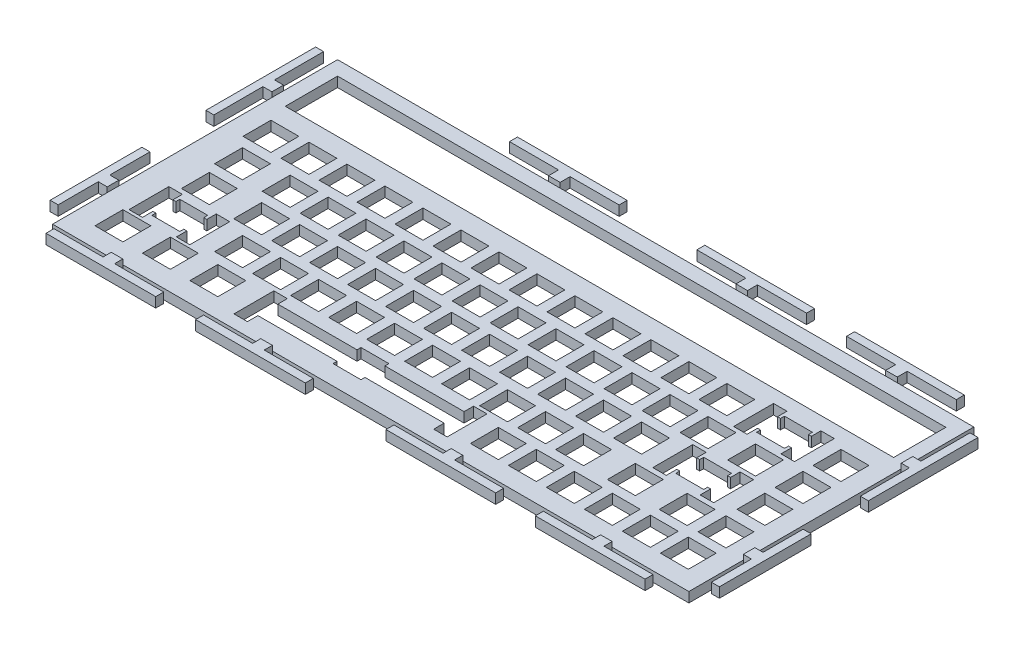
SolidWorks part; units mm, degrees
ref_plane "Front Plane" through (0, 0, 0) normal (0, 0, 1) x (1, 0, 0)
ref_plane "Top Plane" through (0, 0, 0) normal (0, 1, 0) x (1, 0, 0)
ref_plane "Right Plane" through (0, 0, 0) normal (1, 0, 0) x (0, 0, -1)
sketch "Sketch1" plane through (0, 0, 0) normal (0, 1, 0) x (1, 0, 0)
  line L2 (-75.7545, 37.9956) -> (-61.7545, 37.9956)
  line L3 (-94.8265, 37.9956) -> (-80.8265, 37.9956)
  line L4 (-94.8265, 37.9956) -> (-94.8265, 51.9956)
  line L5 (-94.8265, 51.9956) -> (-80.8265, 51.9956)
  line L6 (-80.8265, 37.9956) -> (-80.8265, 51.9956)
  line L7 (-75.7545, 37.9956) -> (-75.7545, 51.9956)
  line L8 (-75.7545, 51.9956) -> (-61.7545, 51.9956)
  line L9 (-61.7545, 37.9956) -> (-61.7545, 51.9956)
  line L10 (133.7495, 37.9956) -> (147.7495, 37.9956)
  line L11 (-37.6545, 37.9956) -> (-23.6545, 37.9956)
  line L12 (-56.7045, 37.9956) -> (-42.7045, 37.9956)
  line L13 (-56.7045, 37.9956) -> (-56.7045, 51.9956)
  line L14 (-56.7045, 51.9956) -> (-42.7045, 51.9956)
  line L15 (-42.7045, 37.9956) -> (-42.7045, 51.9956)
  line L16 (-37.6545, 37.9956) -> (-37.6545, 51.9956)
  line L17 (-37.6545, 51.9956) -> (-23.6545, 51.9956)
  line L18 (-23.6545, 37.9956) -> (-23.6545, 51.9956)
  line L19 (133.7495, 37.9956) -> (133.7495, 51.9956)
  line L20 (133.7495, 51.9956) -> (147.7495, 51.9956)
  line L21 (0.4455, 37.9956) -> (14.4455, 37.9956)
  line L22 (-18.6045, 37.9956) -> (-4.6045, 37.9956)
  line L23 (-18.6045, 37.9956) -> (-18.6045, 51.9956)
  line L24 (-18.6045, 51.9956) -> (-4.6045, 51.9956)
  line L25 (-4.6045, 37.9956) -> (-4.6045, 51.9956)
  line L26 (0.4455, 37.9956) -> (0.4455, 51.9956)
  line L27 (0.4455, 51.9956) -> (14.4455, 51.9956)
  line L28 (14.4455, 37.9956) -> (14.4455, 51.9956)
  line L29 (147.7495, 37.9956) -> (147.7495, 51.9956)
  line L30 (38.5455, 37.9956) -> (52.5455, 37.9956)
  line L31 (19.4955, 37.9956) -> (33.4955, 37.9956)
  line L32 (19.4955, 37.9956) -> (19.4955, 51.9956)
  line L33 (19.4955, 51.9956) -> (33.4955, 51.9956)
  line L34 (33.4955, 37.9956) -> (33.4955, 51.9956)
  line L35 (38.5455, 37.9956) -> (38.5455, 51.9956)
  line L36 (38.5455, 51.9956) -> (52.5455, 51.9956)
  line L37 (52.5455, 37.9956) -> (52.5455, 51.9956)
  line L38 (147.7495, 44.9956) -> (154.1495, 44.9956) construction
  line L39 (167.1835, 18.9456) -> (181.1835, 18.9456)
  line L40 (167.1835, 18.9456) -> (167.1835, 32.9456)
  line L41 (76.6455, 37.9956) -> (90.6455, 37.9956)
  line L42 (57.5955, 37.9956) -> (71.5955, 37.9956)
  line L43 (57.5955, 37.9956) -> (57.5955, 51.9956)
  line L44 (57.5955, 51.9956) -> (71.5955, 51.9956)
  line L45 (71.5955, 37.9956) -> (71.5955, 51.9956)
  line L46 (76.6455, 37.9956) -> (76.6455, 51.9956)
  line L47 (76.6455, 51.9956) -> (90.6455, 51.9956)
  line L48 (90.6455, 37.9956) -> (90.6455, 51.9956)
  line L49 (167.1835, 32.9456) -> (181.1835, 32.9456)
  line L50 (114.7225, 37.9956) -> (128.7225, 37.9956)
  line L51 (95.6955, 37.9956) -> (109.6955, 37.9956)
  line L52 (95.6955, 37.9956) -> (95.6955, 51.9956)
  line L53 (95.6955, 51.9956) -> (109.6955, 51.9956)
  line L54 (109.6955, 37.9956) -> (109.6955, 51.9956)
  line L55 (114.7225, 37.9956) -> (114.7225, 51.9956)
  line L56 (114.7225, 51.9956) -> (128.7225, 51.9956)
  line L57 (128.7225, 37.9956) -> (128.7225, 51.9956)
  line L58 (181.1835, 18.9456) -> (181.1835, 32.9456)
  line L59 (157.3735, 25.9456) -> (167.1835, 25.9456) construction
  line L73 (162.3995, 52.2456) -> (176.3995, 52.2456)
  line L75 (176.3995, 38.2456) -> (162.3995, 38.2456)
  line L77 (176.3995, 52.2456) -> (176.3995, 50.2456)
  line L78 (176.3995, 50.2456) -> (177.8995, 50.2456)
  line L79 (177.8995, 50.2456) -> (177.8995, 54.9956)
  line L80 (177.8995, 54.9956) -> (184.6495, 54.9956)
  line L81 (184.6495, 54.9956) -> (184.6495, 34.9956)
  line L82 (184.6495, 34.9956) -> (177.8995, 34.9956)
  line L83 (177.8995, 34.9956) -> (177.8995, 40.2456)
  line L84 (177.8995, 40.2456) -> (176.3995, 40.2456)
  line L85 (176.3995, 40.2456) -> (176.3995, 38.2456)
  line L86 (162.3995, 52.2456) -> (162.3995, 50.2456)
  line L87 (160.8995, 54.9956) -> (160.8995, 50.2456)
  line L88 (160.8995, 50.2456) -> (162.3995, 50.2456)
  line L89 (160.8995, 54.9956) -> (154.1495, 54.9956)
  line L90 (154.1495, 54.9956) -> (154.1495, 34.9956)
  line L91 (154.1495, 34.9956) -> (160.8995, 34.9956)
  line L92 (160.8995, 34.9956) -> (160.8995, 40.2456)
  line L93 (160.8995, 40.2456) -> (162.3995, 40.2456)
  line L94 (162.3995, 40.2456) -> (162.3995, 38.2456)
  line L116 (-47.1265, 18.9456) -> (-33.1265, 18.9456)
  line L117 (-66.1765, 18.9456) -> (-52.1765, 18.9456)
  line L118 (-66.1765, 18.9456) -> (-66.1765, 32.9456)
  line L119 (-66.1765, 32.9456) -> (-52.1765, 32.9456)
  line L120 (-52.1765, 18.9456) -> (-52.1765, 32.9456)
  line L121 (-47.1265, 18.9456) -> (-47.1265, 32.9456)
  line L122 (-47.1265, 32.9456) -> (-33.1265, 32.9456)
  line L123 (-33.1265, 18.9456) -> (-33.1265, 32.9456)
  line L125 (-9.0515, 18.9456) -> (4.9485, 18.9456)
  line L126 (-28.0765, 18.9456) -> (-14.0765, 18.9456)
  line L127 (-28.0765, 18.9456) -> (-28.0765, 32.9456)
  line L128 (-28.0765, 32.9456) -> (-14.0765, 32.9456)
  line L129 (-14.0765, 18.9456) -> (-14.0765, 32.9456)
  line L130 (-9.0515, 18.9456) -> (-9.0515, 32.9456)
  line L131 (-9.0515, 32.9456) -> (4.9485, 32.9456)
  line L132 (4.9485, 18.9456) -> (4.9485, 32.9456)
  line L135 (29.0735, 18.9456) -> (43.0735, 18.9456)
  line L136 (9.9485, 18.9456) -> (23.9485, 18.9456)
  line L137 (9.9485, 18.9456) -> (9.9485, 32.9456)
  line L138 (9.9485, 32.9456) -> (23.9485, 32.9456)
  line L139 (23.9485, 18.9456) -> (23.9485, 32.9456)
  line L140 (29.0735, 18.9456) -> (29.0735, 32.9456)
  line L141 (29.0735, 32.9456) -> (43.0735, 32.9456)
  line L142 (43.0735, 18.9456) -> (43.0735, 32.9456)
  line L144 (67.1485, 18.9456) -> (81.1485, 18.9456)
  line L145 (48.1235, 18.9456) -> (62.1235, 18.9456)
  line L146 (48.1235, 18.9456) -> (48.1235, 32.9456)
  line L147 (48.1235, 32.9456) -> (62.1235, 32.9456)
  line L148 (62.1235, 18.9456) -> (62.1235, 32.9456)
  line L149 (67.1485, 18.9456) -> (67.1485, 32.9456)
  line L150 (67.1485, 32.9456) -> (81.1485, 32.9456)
  line L151 (81.1485, 18.9456) -> (81.1485, 32.9456)
  line L152 (159.9865, 14.1456) -> (173.9865, 14.1456)
  line L153 (-42.3635, -0.1044) -> (-28.3635, -0.1044)
  line L154 (-61.4135, -0.1044) -> (-47.4135, -0.1044)
  line L155 (105.2735, 18.9456) -> (119.2735, 18.9456)
  line L156 (86.2235, 18.9456) -> (100.2235, 18.9456)
  line L157 (86.2235, 18.9456) -> (86.2235, 32.9456)
  line L158 (86.2235, 32.9456) -> (100.2235, 32.9456)
  line L159 (100.2235, 18.9456) -> (100.2235, 32.9456)
  line L160 (105.2735, 18.9456) -> (105.2735, 32.9456)
  line L161 (105.2735, 32.9456) -> (119.2735, 32.9456)
  line L162 (119.2735, 18.9456) -> (119.2735, 32.9456)
  line L163 (-61.4135, -0.1044) -> (-61.4135, 13.8956)
  line L172 (-94.8265, 37.9956) -> (-94.8265, 32.9456) construction
  line L173 (-61.4135, 13.8956) -> (-47.4135, 13.8956)
  line L174 (-47.4135, -0.1044) -> (-47.4135, 13.8956)
  line L175 (-90.0635, 18.9456) -> (-76.0635, 18.9456)
  line L176 (-90.0635, 18.9456) -> (-90.0635, 32.9456)
  line L177 (-90.0635, 32.9456) -> (-76.0635, 32.9456)
  line L178 (-76.0635, 18.9456) -> (-76.0635, 32.9456)
  line L179 (-94.8265, 32.9456) -> (-90.0635, 32.9456) construction
  line L180 (124.3235, 18.9456) -> (138.3235, 18.9456)
  line L185 (124.3235, 18.9456) -> (124.3235, 32.9456)
  line L186 (124.3235, 32.9456) -> (138.3235, 32.9456)
  line L187 (138.3235, 18.9456) -> (138.3235, 32.9456)
  line L188 (-42.3635, -0.1044) -> (-42.3635, 13.8956)
  line L189 (143.3735, 18.9456) -> (157.3735, 18.9456)
  line L190 (143.3735, 18.9456) -> (143.3735, 32.9456)
  line L191 (143.3735, 32.9456) -> (157.3735, 32.9456)
  line L192 (157.3735, 18.9456) -> (157.3735, 32.9456)
  line L193 (-42.3635, 13.8956) -> (-28.3635, 13.8956)
  line L194 (-28.3635, -0.1044) -> (-28.3635, 13.8956)
  line L195 (-4.2635, -0.1044) -> (9.7365, -0.1044)
  line L196 (-23.3135, -0.1044) -> (-9.3135, -0.1044)
  line L197 (-23.3135, -0.1044) -> (-23.3135, 13.8956)
  line L198 (-23.3135, 13.8956) -> (-9.3135, 13.8956)
  line L199 (-9.3135, -0.1044) -> (-9.3135, 13.8956)
  line L200 (-4.2635, -0.1044) -> (-4.2635, 13.8956)
  line L201 (-4.2635, 13.8956) -> (9.7365, 13.8956)
  line L202 (9.7365, -0.1044) -> (9.7365, 13.8956)
  line L203 (33.8365, -0.1044) -> (47.8365, -0.1044)
  line L204 (14.7865, -0.1044) -> (28.7865, -0.1044)
  line L205 (14.7865, -0.1044) -> (14.7865, 13.8956)
  line L206 (14.7865, 13.8956) -> (28.7865, 13.8956)
  line L207 (28.7865, -0.1044) -> (28.7865, 13.8956)
  line L208 (33.8365, -0.1044) -> (33.8365, 13.8956)
  line L209 (33.8365, 13.8956) -> (47.8365, 13.8956)
  line L210 (47.8365, -0.1044) -> (47.8365, 13.8956)
  line L211 (71.9365, -0.1044) -> (85.9365, -0.1044)
  line L212 (52.8865, -0.1044) -> (66.8865, -0.1044)
  line L213 (52.8865, -0.1044) -> (52.8865, 13.8956)
  line L214 (52.8865, 13.8956) -> (66.8865, 13.8956)
  line L215 (66.8865, -0.1044) -> (66.8865, 13.8956)
  line L216 (71.9365, -0.1044) -> (71.9365, 13.8956)
  line L217 (71.9365, 13.8956) -> (85.9365, 13.8956)
  line L218 (85.9365, -0.1044) -> (85.9365, 13.8956)
  line L219 (110.0365, -0.1044) -> (124.0365, -0.1044)
  line L220 (90.9865, -0.1044) -> (104.9865, -0.1044)
  line L221 (90.9865, -0.1044) -> (90.9865, 13.8956)
  line L222 (90.9865, 13.8956) -> (104.9865, 13.8956)
  line L223 (104.9865, -0.1044) -> (104.9865, 13.8956)
  line L224 (110.0365, -0.1044) -> (110.0365, 13.8956)
  line L225 (110.0365, 13.8956) -> (124.0365, 13.8956)
  line L226 (124.0365, -0.1044) -> (124.0365, 13.8956)
  line L227 (-87.6075, -0.1044) -> (-73.6075, -0.1044)
  line L228 (-87.6075, -0.1044) -> (-87.6075, 13.8956)
  line L229 (-87.6075, 13.8956) -> (-73.6075, 13.8956)
  line L230 (-73.6075, -0.1044) -> (-73.6075, 13.8956)
  line L231 (-90.0635, 18.9456) -> (-90.0635, 13.8956) construction
  line L232 (129.0865, -0.1044) -> (143.0865, -0.1044)
  line L233 (129.0865, -0.1044) -> (129.0865, 13.8956)
  line L234 (129.0865, 13.8956) -> (143.0865, 13.8956)
  line L235 (143.0865, -0.1044) -> (143.0865, 13.8956)
  line L240 (-90.0635, 13.8956) -> (-87.6075, 13.8956) construction
  line L241 (173.9865, 0.1456) -> (159.9865, 0.1456)
  line L242 (173.9865, 14.1456) -> (173.9865, 12.1456)
  line L243 (173.9865, 12.1456) -> (175.4865, 12.1456)
  line L244 (175.4865, 12.1456) -> (175.4865, 16.8956)
  line L245 (175.4865, 16.8956) -> (182.2365, 16.8956)
  line L246 (182.2365, 16.8956) -> (182.2365, -3.1044)
  line L247 (182.2365, -3.1044) -> (175.4865, -3.1044)
  line L248 (175.4865, -3.1044) -> (175.4865, 2.1456)
  line L249 (175.4865, 2.1456) -> (173.9865, 2.1456)
  line L250 (173.9865, 2.1456) -> (173.9865, 0.1456)
  line L251 (159.9865, 14.1456) -> (159.9865, 12.1456)
  line L252 (158.4865, 16.8956) -> (158.4865, 12.1456)
  line L253 (158.4865, 12.1456) -> (159.9865, 12.1456)
  line L254 (158.4865, 16.8956) -> (151.7365, 16.8956)
  line L255 (151.7365, 16.8956) -> (151.7365, -3.1044)
  line L256 (151.7365, -3.1044) -> (158.4865, -3.1044)
  line L257 (158.4865, -3.1044) -> (158.4865, 2.1456)
  line L258 (158.4865, 2.1456) -> (159.9865, 2.1456)
  line L259 (159.9865, 2.1456) -> (159.9865, 0.1456)
  line L260 (143.0865, 12.1456) -> (151.7365, 12.1456) construction
  line L262 (-32.8385, -19.1544) -> (-18.8385, -19.1544)
  line L263 (-51.8885, -19.1544) -> (-37.8885, -19.1544)
  line L264 (-51.8885, -19.1544) -> (-51.8885, -5.1544)
  line L265 (-51.8885, -5.1544) -> (-37.8885, -5.1544)
  line L266 (-37.8885, -19.1544) -> (-37.8885, -5.1544)
  line L267 (-32.8385, -19.1544) -> (-32.8385, -5.1544)
  line L268 (-32.8385, -5.1544) -> (-18.8385, -5.1544)
  line L269 (-18.8385, -19.1544) -> (-18.8385, -5.1544)
  line L270 (5.2615, -19.1544) -> (19.2615, -19.1544)
  line L271 (-13.7885, -19.1544) -> (0.2115, -19.1544)
  line L272 (-13.7885, -19.1544) -> (-13.7885, -5.1544)
  line L273 (-13.7885, -5.1544) -> (0.2115, -5.1544)
  line L274 (0.2115, -19.1544) -> (0.2115, -5.1544)
  line L275 (5.2615, -19.1544) -> (5.2615, -5.1544)
  line L276 (5.2615, -5.1544) -> (19.2615, -5.1544)
  line L277 (19.2615, -19.1544) -> (19.2615, -5.1544)
  line L278 (43.3615, -19.1544) -> (57.3615, -19.1544)
  line L279 (24.3115, -19.1544) -> (38.3115, -19.1544)
  line L280 (24.3115, -19.1544) -> (24.3115, -5.1544)
  line L281 (24.3115, -5.1544) -> (38.3115, -5.1544)
  line L282 (38.3115, -19.1544) -> (38.3115, -5.1544)
  line L283 (43.3615, -19.1544) -> (43.3615, -5.1544)
  line L284 (43.3615, -5.1544) -> (57.3615, -5.1544)
  line L285 (57.3615, -19.1544) -> (57.3615, -5.1544)
  line L286 (81.4615, -19.6544) -> (95.4615, -19.6544)
  line L287 (62.4115, -19.6544) -> (76.4115, -19.6544)
  line L288 (62.4115, -19.6544) -> (62.4115, -5.6544)
  line L289 (62.4115, -5.6544) -> (76.4115, -5.6544)
  line L290 (76.4115, -19.6544) -> (76.4115, -5.6544)
  line L291 (81.4615, -19.6544) -> (81.4615, -5.6544)
  line L292 (81.4615, -5.6544) -> (95.4615, -5.6544)
  line L293 (95.4615, -19.6544) -> (95.4615, -5.6544)
  line L294 (119.5615, -19.6544) -> (133.5615, -19.6544)
  line L295 (100.5115, -19.6544) -> (114.5115, -19.6544)
  line L296 (100.5115, -19.6544) -> (100.5115, -5.6544)
  line L297 (100.5115, -5.6544) -> (114.5115, -5.6544)
  line L298 (114.5115, -19.6544) -> (114.5115, -5.6544)
  line L299 (119.5615, -19.6544) -> (119.5615, -5.6544)
  line L300 (119.5615, -5.6544) -> (133.5615, -5.6544)
  line L301 (133.5615, -19.6544) -> (133.5615, -5.6544)
  line L306 (-83.3445, -5.1544) -> (-69.3445, -5.1544)
  line L307 (145.5235, -19.6544) -> (159.5235, -19.6544)
  line L308 (145.5235, -19.6544) -> (145.5235, -5.6544)
  line L309 (145.5235, -5.6544) -> (159.5235, -5.6544)
  line L310 (159.5235, -19.6544) -> (159.5235, -5.6544)
  line L311 (-69.3445, -19.1544) -> (-83.3445, -19.1544)
  line L331 (171.4855, -19.6544) -> (185.4855, -19.6544)
  line L332 (171.4855, -19.6544) -> (171.4855, -5.6544)
  line L333 (171.4855, -5.6544) -> (185.4855, -5.6544)
  line L334 (185.4855, -19.6544) -> (185.4855, -5.6544)
  line L335 (159.5235, -12.6544) -> (171.4855, -12.6544) construction
  line L336 (-61.4135, -0.1044) -> (-61.4135, -5.1544) construction
  line L337 (-61.4135, -5.1544) -> (-51.8885, -5.1544) construction
  line L338 (-104.4215, 94.9896) -> (-117.5239, 94.9896) construction
  line L339 (-97.2765, 61.6456) -> (207.7235, 61.6456)
  line L340 (190.9955, 18.9456) -> (204.9955, 18.9456)
  line L341 (190.9955, 18.9456) -> (190.9955, 32.9456)
  line L342 (190.9955, 32.9456) -> (204.9955, 32.9456)
  line L343 (204.9955, 18.9456) -> (204.9955, 32.9456)
  line L344 (181.1835, 25.9456) -> (190.9955, 25.9456) construction
  line L345 (190.9745, 37.9956) -> (204.9745, 37.9956)
  line L346 (190.9745, 37.9956) -> (190.9745, 51.9956)
  line L347 (190.9745, 51.9956) -> (204.9745, 51.9956)
  line L348 (204.9745, 37.9956) -> (204.9745, 51.9956)
  line L349 (184.6495, 44.9956) -> (190.9745, 44.9956) construction
  line L350 (190.9425, -0.1044) -> (204.9425, -0.1044)
  line L351 (190.9425, -0.1044) -> (190.9425, 13.8956)
  line L352 (190.9425, 13.8956) -> (204.9425, 13.8956)
  line L353 (204.9425, -0.1044) -> (204.9425, 13.8956)
  line L354 (182.2365, 6.8956) -> (190.9425, 6.8956) construction
  line L355 (190.9855, -19.6544) -> (204.9855, -19.6544)
  line L356 (190.9855, -19.6544) -> (190.9855, -5.6544)
  line L357 (190.9855, -5.6544) -> (204.9855, -5.6544)
  line L358 (204.9855, -19.6544) -> (204.9855, -5.6544)
  line L359 (185.4855, -12.6544) -> (190.9855, -12.6544) construction
  line L360 (-69.3445, -5.1544) -> (-69.3445, -7.1544)
  line L361 (-69.3445, -7.1544) -> (-67.8445, -7.1544)
  line L362 (-67.8445, -7.1544) -> (-67.8445, -2.4044)
  line L363 (-67.8445, -2.4044) -> (-61.0945, -2.4044)
  line L364 (-61.0945, -2.4044) -> (-61.0945, -22.4044)
  line L365 (-61.0945, -22.4044) -> (-67.8445, -22.4044)
  line L366 (-67.8445, -22.4044) -> (-67.8445, -17.1544)
  line L367 (-67.8445, -17.1544) -> (-69.3445, -17.1544)
  line L368 (-69.3445, -17.1544) -> (-69.3445, -19.1544)
  line L369 (-83.3445, -5.1544) -> (-83.3445, -7.1544)
  line L370 (-84.8445, -2.4044) -> (-84.8445, -7.1544)
  line L371 (-84.8445, -7.1544) -> (-83.3445, -7.1544)
  line L372 (-84.8445, -2.4044) -> (-91.5945, -2.4044)
  line L373 (-91.5945, -2.4044) -> (-91.5945, -22.4044)
  line L374 (-91.5945, -22.4044) -> (-84.8445, -22.4044)
  line L375 (-84.8445, -22.4044) -> (-84.8445, -17.1544)
  line L376 (-84.8445, -17.1544) -> (-83.3445, -17.1544)
  line L377 (-83.3445, -17.1544) -> (-83.3445, -19.1544)
  line L378 (-93.0945, -37.9544) -> (-79.0945, -37.9544)
  line L379 (-93.0945, -37.9544) -> (-93.0945, -23.9544)
  line L380 (-93.0945, -23.9544) -> (-79.0945, -23.9544)
  line L381 (-79.0945, -37.9544) -> (-79.0945, -23.9544)
  line L382 (-69.2945, -37.9544) -> (-55.2945, -37.9544)
  line L383 (-69.2945, -37.9544) -> (-69.2945, -23.9544)
  line L384 (-69.2945, -23.9544) -> (-55.2945, -23.9544)
  line L385 (-55.2945, -37.9544) -> (-55.2945, -23.9544)
  line L390 (-45.4945, -37.9544) -> (-31.4945, -37.9544)
  line L391 (-45.4945, -37.9544) -> (-45.4945, -23.9544)
  line L392 (-45.4945, -23.9544) -> (-31.4945, -23.9544)
  line L393 (-31.4945, -37.9544) -> (-31.4945, -23.9544)
  line L394 (-55.2945, -23.9544) -> (-45.4945, -23.9544) construction
  line L395 (26.4395, -24.1144) -> (40.4395, -24.1144)
  line L396 (40.4395, -38.1144) -> (26.4395, -38.1144)
  line L397 (40.4395, -24.1144) -> (40.4395, -26.1144)
  line L398 (40.4395, -26.1144) -> (80.1235, -26.1144)
  line L399 (80.1235, -26.1144) -> (80.1235, -21.3644)
  line L400 (80.1235, -21.3644) -> (86.8735, -21.3644)
  line L401 (86.8735, -21.3644) -> (86.8735, -41.3644)
  line L402 (86.8735, -41.3644) -> (80.1235, -41.3644)
  line L403 (80.1235, -41.3644) -> (80.1235, -36.1144)
  line L404 (80.1235, -36.1144) -> (40.4395, -36.1144)
  line L405 (40.4395, -36.1144) -> (40.4395, -38.1144)
  line L406 (26.4395, -24.1144) -> (26.4395, -26.1144)
  line L407 (-13.2445, -21.3644) -> (-13.2445, -26.1144)
  line L408 (-13.2445, -26.1144) -> (26.4395, -26.1144)
  line L409 (-13.2445, -21.3644) -> (-19.9945, -21.3644)
  line L410 (-19.9945, -21.3644) -> (-19.9945, -41.3644)
  line L411 (-19.9945, -41.3644) -> (-13.2445, -41.3644)
  line L412 (-13.2445, -41.3644) -> (-13.2445, -36.1144)
  line L413 (-13.2445, -36.1144) -> (26.4395, -36.1144)
  line L414 (26.4395, -36.1144) -> (26.4395, -38.1144)
  line L415 (95.5435, -38.3644) -> (109.5435, -38.3644)
  line L416 (95.5435, -38.3644) -> (95.5435, -24.3644)
  line L417 (95.5435, -24.3644) -> (109.5435, -24.3644)
  line L418 (109.5435, -38.3644) -> (109.5435, -24.3644)
  line L419 (86.8735, -31.3644) -> (95.5435, -31.3644) construction
  line L420 (114.5935, -38.3644) -> (128.5935, -38.3644)
  line L421 (114.5935, -38.3644) -> (114.5935, -24.3644)
  line L422 (114.5935, -24.3644) -> (128.5935, -24.3644)
  line L423 (128.5935, -38.3644) -> (128.5935, -24.3644)
  line L424 (114.5935, -31.3644) -> (109.5435, -31.3644) construction
  line L425 (133.6435, -38.3644) -> (147.6435, -38.3644)
  line L426 (133.6435, -38.3644) -> (133.6435, -24.3644)
  line L427 (133.6435, -24.3644) -> (147.6435, -24.3644)
  line L428 (147.6435, -38.3644) -> (147.6435, -24.3644)
  line L429 (152.6935, -38.3644) -> (166.6935, -38.3644)
  line L430 (152.6935, -38.3644) -> (152.6935, -24.3644)
  line L431 (152.6935, -24.3644) -> (166.6935, -24.3644)
  line L432 (166.6935, -38.3644) -> (166.6935, -24.3644)
  line L433 (171.7435, -38.3644) -> (185.7435, -38.3644)
  line L434 (171.7435, -38.3644) -> (171.7435, -24.3644)
  line L435 (171.7435, -24.3644) -> (185.7435, -24.3644)
  line L436 (185.7435, -38.3644) -> (185.7435, -24.3644)
  line L437 (190.7935, -38.3644) -> (204.7935, -38.3644)
  line L438 (190.7935, -38.3644) -> (190.7935, -24.3644)
  line L439 (190.7935, -24.3644) -> (204.7935, -24.3644)
  line L440 (204.7935, -38.3644) -> (204.7935, -24.3644)
  line L441 (-97.2765, 61.6456) -> (-97.2765, 87.8456)
  line L442 (-97.2765, 87.8456) -> (207.7235, 87.8456)
  line L443 (207.7235, 61.6456) -> (207.7235, 87.8456)
  line L444 (-104.4215, 94.9896) -> (214.5785, 94.9896)
  line L445 (-104.4215, 94.9896) -> (-104.4215, -47.8854)
  line L446 (-104.4215, -47.8854) -> (214.5785, -47.8854)
  line L447 (214.5785, 94.9896) -> (214.5785, -47.8854)
  line L448 (-117.5239, 94.9896) -> (-117.5239, 25.8096) construction
  line L449 (-104.4215, -47.8854) -> (-117.5239, -47.8854) construction
  line L450 (-117.5239, -47.8854) -> (-117.5239, 14.6046) construction
  line L451 (-150.5498, 25.8096) -> (-98.6233, 25.8096) construction
  line L452 (-150.5498, 14.6046) -> (-97.2765, 14.6046) construction
  line L453 (-104.4215, 94.9896) -> (-104.4215, 60.3996) construction
  point P115 (128.7225, 44.9956)
  point P116 (154.1495, 44.9956)
  dimension "D1" = 14
  dimension "D2" = 20
  dimension "D3" = 4.75
  dimension "D4" = 6.75
  dimension "D5" = 1.5
  dimension "D6" = 2
  dimension "D13" = 14
  dimension "D14" = 14
  dimension "D15" = 5.072
  dimension "D16" = 14
  dimension "D17" = 5.05
  dimension "D18" = 5.05
  dimension "D19" = 14
  dimension "D20" = 4.763
  dimension "D21" = 5.05
  dimension "D22" = 9.887
  dimension "D23" = 26.2
  dimension "D24" = 14
  dimension "D25" = 14
  dimension "D26" = 5.05
  dimension "D27" = 5.05
  dimension "D28" = 5.05
  dimension "D29" = 5.05
  dimension "D30" = 5.05
  dimension "D31" = 5.05
  dimension "D32" = 5.05
  dimension "D33" = 5.05
  dimension "D34" = 5.05
  dimension "D35" = 5.027
  dimension "D36" = 5.05
  dimension "D37" = 5.05
  dimension "D38" = 5.025
  dimension "D39" = 5
  dimension "D40" = 5.125
  dimension "D41" = 5.05
  dimension "D42" = 5.025
  dimension "D43" = 5.075
  dimension "D44" = 5.05
  dimension "D45" = 5.05
  dimension "D46" = 5.027
  dimension "D47" = 14.65
  dimension "D48" = 14
  dimension "D49" = 9.81
  dimension "D50" = 12.194
  dimension "D51" = 5.05
  dimension "D52" = 5.05
  dimension "D53" = 5.05
  dimension "D54" = 5.05
  dimension "D55" = 5.05
  dimension "D56" = 5.05
  dimension "D57" = 5.05
  dimension "D58" = 5.05
  dimension "D59" = 5.05
  dimension "D60" = 5.05
  dimension "D61" = 14
  dimension "D62" = 20
  dimension "D63" = 5.05
  dimension "D64" = 2.456
  dimension "D65" = 4.75
  dimension "D66" = 6.75
  dimension "D67" = 1.5
  dimension "D68" = 2
  dimension "D69" = 16.9
  dimension "D70" = 14
  dimension "D71" = 5.05
  dimension "D72" = 5.05
  dimension "D73" = 5.05
  dimension "D74" = 5.05
  dimension "D75" = 5.05
  dimension "D76" = 5.05
  dimension "D77" = 5.05
  dimension "D78" = 5.05
  dimension "D79" = 5.05
  dimension "D80" = 11.962
  dimension "D81" = 20
  dimension "D82" = 14
  dimension "D83" = 11.962
  dimension "D84" = 14
  dimension "D85" = 14
  dimension "D86" = 9.812
  dimension "D87" = 14
  dimension "D88" = 14.575
  dimension "D89" = 4.75
  dimension "D90" = 14
  dimension "D91" = 6.75
  dimension "D92" = 14
  dimension "D93" = 16.956
  dimension "D94" = 14
  dimension "D95" = 5.5
  dimension "D96" = 5.05
  dimension "D97" = 5.05
  dimension "D98" = 9.525
  dimension "D99" = 1.5
  dimension "D100" = 2
  dimension "D101" = 5.05
  dimension "D102" = 9.206
  dimension "D103" = 5.05
  dimension "D104" = 14
  dimension "D105" = 14
  dimension "D106" = 14
  dimension "D107" = 14
  dimension "D108" = 1.5
  dimension "D109" = 9.8
  dimension "D110" = 5.05
  dimension "D111" = 9.8
  dimension "D112" = 5.05
  dimension "D113" = 5.05
  dimension "D114" = 14
  dimension "D115" = 14
  dimension "D116" = 20
  dimension "D117" = 4.75
  dimension "D118" = 6.75
  dimension "D119" = 39.684
  dimension "D120" = 2
  dimension "D121" = 5.05
  dimension "D122" = 11.5
  dimension "D123" = 14
  dimension "D124" = 8.67
  dimension "D125" = 5.25
  dimension "D126" = 14
  dimension "D127" = 5.05
  dimension "D128" = 14
  dimension "D129" = 14
  dimension "D130" = 14
  dimension "D131" = 14
  dimension "D132" = 5.05
  dimension "D133" = 5.05
  dimension "D134" = 5.05
  dimension "D135" = 5.05
  dimension "D136" = 4.8
  dimension "D137" = 5.25
  dimension "D138" = 5.25
  dimension "D139" = 5.25
  dimension "D140" = 305
  dimension "D141" = 9.65
  dimension "D142" = 142.875
  dimension "D143" = 319
  dimension "D144" = 7.144
  dimension "D145" = 7.145
  dimension "D146" = 2.45
  dimension "D147" = 69.18
  dimension "D148" = 62.49
extrude "Boss-Extrude2" add sketch "Sketch1" along normal mid plane 5
sketch "Sketch2" plane through (0, 2.5, 0) normal (0, 1, 0) x (1, 0, 0)
  line L0 (-104.4215, 25.7896) -> (-104.4215, 14.6146) construction
  line L1 (-104.4215, -47.8854) -> (-104.4215, -20.4854) construction
  line L2 (-104.4215, 94.9896) -> (-104.4215, -47.8854) construction
  line L14 (-107.4215, 20.2021) -> (-104.4215, 20.2021) construction
  line L16 (-107.4215, 31.2421) -> (-107.4215, 9.1621) construction
  line L25 (214.5785, 64.3896) -> (214.5785, 58.5896)
  line L26 (55.1185, 125.3194) -> (55.1185, -78.0627) construction
  line L44 (214.5785, 58.5896) -> (218.6785, 58.5896)
  line L45 (218.6785, 58.5896) -> (218.6785, 33.9896)
  line L46 (218.6785, 33.9896) -> (222.6785, 33.9896)
  line L47 (222.6785, 33.9896) -> (222.6785, 88.9896)
  line L48 (55.0785, 94.9896) -> (55.0785, -47.8854) construction
  line L49 (214.5785, 94.9896) -> (-104.4215, 94.9896) construction
  line L50 (-104.4215, -47.8854) -> (214.5785, -47.8854) construction
  line L51 (55.1185, 23.6283) -> (270.1989, 23.6283) construction
  line L52 (55.1185, 23.6283) -> (-168.679, 23.6283) construction
  line L55 (45.7235, 94.9896) -> (56.8285, 94.9896) construction
  line L56 (51.276, 94.9896) -> (51.276, 98.9896) construction
  line L57 (40.236, 98.9896) -> (62.316, 98.9896) construction
  line L74 (222.6785, 88.9896) -> (218.6785, 88.9896)
  line L75 (214.5785, 94.9896) -> (176.1966, 94.9896) construction
  line L124 (55.0785, -47.8854) -> (95.4285, -47.8854) construction
  line L125 (-104.4215, 67.8896) -> (-104.4215, 62.0896)
  line L127 (45.7225, -47.8854) -> (56.8335, -47.8854) construction
  line L128 (51.278, -47.8854) -> (51.278, -52.8854) construction
  line L129 (40.276, -52.8854) -> (62.356, -52.8854) construction
  line L134 (-104.4215, 62.0896) -> (-108.9215, 62.0896)
  line L135 (-108.9215, 62.0896) -> (-108.9215, 37.4896)
  line L136 (-108.9215, 37.4896) -> (-112.9215, 37.4896)
  line L137 (-112.9215, 37.4896) -> (-112.9215, 92.4896)
  line L138 (-112.9215, 92.4896) -> (-108.9215, 92.4896)
  line L139 (-108.9215, 92.4896) -> (-108.9215, 67.8896)
  line L140 (-108.9215, 67.8896) -> (-104.4215, 67.8896)
  line L141 (-104.4215, 94.9896) -> (-104.4215, 67.8896) construction
  line L142 (-104.4215, -14.6854) -> (-104.4215, -20.4854)
  line L143 (-104.4215, -20.4854) -> (-108.9215, -20.4854)
  line L144 (-108.9215, -20.4854) -> (-108.9215, -40.5854)
  line L145 (-108.9215, -40.5854) -> (-112.9215, -40.5854)
  line L146 (-112.9215, -40.5854) -> (-112.9215, 5.4146)
  line L147 (-112.9215, 5.4146) -> (-108.9215, 5.4146)
  line L148 (-108.9215, 5.4146) -> (-108.9215, -14.6854)
  line L149 (-108.9215, -14.6854) -> (-104.4215, -14.6854)
  line L150 (1.3585, 94.9896) -> (7.1585, 94.9896)
  line L151 (7.1585, 94.9896) -> (7.1585, 99.9896)
  line L152 (7.1585, 99.9896) -> (31.7585, 99.9896)
  line L153 (31.7585, 99.9896) -> (31.7585, 103.9896)
  line L154 (31.7585, 103.9896) -> (-23.2415, 103.9896)
  line L155 (-23.2415, 103.9896) -> (-23.2415, 99.9896)
  line L156 (-23.2415, 99.9896) -> (1.3585, 99.9896)
  line L157 (1.3585, 99.9896) -> (1.3585, 94.9896)
  line L158 (55.0785, 94.9896) -> (7.1585, 94.9896) construction
  line L166 (-75.0215, -47.8854) -> (-69.2215, -47.8854)
  line L167 (-69.2215, -47.8854) -> (-69.2215, -51.9854)
  line L168 (-69.2215, -51.9854) -> (-44.6215, -51.9854)
  line L169 (-44.6215, -51.9854) -> (-44.6215, -55.9854)
  line L170 (-44.6215, -55.9854) -> (-99.6215, -55.9854)
  line L171 (-99.6215, -55.9854) -> (-99.6215, -51.9854)
  line L172 (-99.6215, -51.9854) -> (-75.0215, -51.9854)
  line L173 (-75.0215, -51.9854) -> (-75.0215, -47.8854)
  line L174 (-0.0215, -47.8854) -> (5.7785, -47.8854)
  line L175 (5.7785, -47.8854) -> (5.7785, -51.9854)
  line L176 (5.7785, -51.9854) -> (30.3785, -51.9854)
  line L177 (30.3785, -51.9854) -> (30.3785, -55.9854)
  line L178 (30.3785, -55.9854) -> (-24.6215, -55.9854)
  line L179 (-24.6215, -55.9854) -> (-24.6215, -51.9854)
  line L180 (-24.6215, -51.9854) -> (-0.0215, -51.9854)
  line L181 (-0.0215, -51.9854) -> (-0.0215, -47.8854)
  line L182 (-104.4215, -47.8854) -> (-75.0215, -47.8854) construction
  line L183 (95.4285, -47.8854) -> (101.2285, -47.8854)
  line L184 (101.2285, -47.8854) -> (101.2285, -51.9854)
  line L185 (101.2285, -51.9854) -> (125.8285, -51.9854)
  line L186 (125.8285, -51.9854) -> (125.8285, -55.9854)
  line L187 (125.8285, -55.9854) -> (70.8285, -55.9854)
  line L188 (70.8285, -55.9854) -> (70.8285, -51.9854)
  line L189 (70.8285, -51.9854) -> (95.4285, -51.9854)
  line L190 (95.4285, -51.9854) -> (95.4285, -47.8854)
  line L191 (170.3285, -47.8854) -> (176.1285, -47.8854)
  line L192 (176.1285, -47.8854) -> (176.1285, -51.9854)
  line L193 (176.1285, -51.9854) -> (200.7285, -51.9854)
  line L194 (200.7285, -51.9854) -> (200.7285, -55.9854)
  line L195 (200.7285, -55.9854) -> (145.7285, -55.9854)
  line L196 (145.7285, -55.9854) -> (145.7285, -51.9854)
  line L197 (145.7285, -51.9854) -> (170.3285, -51.9854)
  line L198 (170.3285, -51.9854) -> (170.3285, -47.8854)
  line L199 (55.0785, -47.8854) -> (5.7785, -47.8854) construction
  line L200 (95.3145, 94.9896) -> (101.1145, 94.9896)
  line L201 (101.1145, 94.9896) -> (101.1145, 99.9896)
  line L202 (101.1145, 99.9896) -> (125.7145, 99.9896)
  line L203 (125.7145, 99.9896) -> (125.7145, 103.9896)
  line L204 (125.7145, 103.9896) -> (70.7145, 103.9896)
  line L205 (70.7145, 103.9896) -> (70.7145, 99.9896)
  line L206 (70.7145, 99.9896) -> (95.3145, 99.9896)
  line L207 (95.3145, 99.9896) -> (95.3145, 94.9896)
  line L208 (170.3966, 94.9896) -> (176.1966, 94.9896)
  line L209 (176.1966, 94.9896) -> (176.1966, 99.9896)
  line L210 (176.1966, 99.9896) -> (200.7966, 99.9896)
  line L211 (200.7966, 99.9896) -> (200.7966, 103.9896)
  line L212 (200.7966, 103.9896) -> (145.7966, 103.9896)
  line L213 (145.7966, 103.9896) -> (145.7966, 99.9896)
  line L214 (145.7966, 99.9896) -> (170.3966, 99.9896)
  line L215 (170.3966, 99.9896) -> (170.3966, 94.9896)
  line L216 (214.5785, -47.8854) -> (176.1285, -47.8854) construction
  line L217 (218.6785, 88.9896) -> (218.6785, 64.3896)
  line L218 (218.6785, 64.3896) -> (214.5785, 64.3896)
  line L219 (214.5785, -14.7854) -> (214.5785, -20.5854)
  line L220 (214.5785, -20.5854) -> (218.6785, -20.5854)
  line L221 (218.6785, -20.5854) -> (218.6785, -40.6854)
  line L222 (218.6785, -40.6854) -> (222.6785, -40.6854)
  line L223 (222.6785, -40.6854) -> (222.6785, 5.3146)
  line L224 (222.6785, 5.3146) -> (218.6785, 5.3146)
  line L225 (218.6785, 5.3146) -> (218.6785, -14.7854)
  line L226 (218.6785, -14.7854) -> (214.5785, -14.7854)
  line L227 (214.5785, 94.9896) -> (214.5785, 64.3896) construction
  line L228 (214.5785, -47.8854) -> (214.5785, 94.9896) construction
  line L229 (214.5785, -47.8854) -> (214.5785, -20.5854) construction
  point P28 (-104.4215, 20.2021)
  point P84 (51.276, 98.9896)
  dimension "D4" = 5.8
  dimension "D5" = 4.5
  dimension "D6" = 55
  dimension "D7" = 22.08
  dimension "D8" = 4
  dimension "D9" = 5.8
  dimension "D10" = 4.5
  dimension "D11" = 4
  dimension "D12" = 46
  dimension "D13" = 27.1
  dimension "D14" = 5.8
  dimension "D15" = 4.1
  dimension "D16" = 4
  dimension "D17" = 27.4
  dimension "D18" = 47.92
  dimension "D19" = 4
  dimension "D20" = 22.08
  dimension "D21" = 40.196
  dimension "D22" = 55
  dimension "D23" = 5.8
  dimension "D24" = 4
  dimension "D25" = 46
  dimension "D26" = 30.6
  dimension "D27" = 27.3
  dimension "D29" = 4.1
  dimension "D31" = 38.45
  dimension "D32" = 5.8
  dimension "D33" = 5
  dimension "D34" = 22.08
  dimension "D35" = 5.8
  dimension "D36" = 5
  dimension "D37" = 4
  dimension "D38" = 55
  dimension "D39" = 40.35
  dimension "D40" = 5.8
  dimension "D41" = 4
  dimension "D42" = 55
  dimension "D43" = 4
  dimension "D44" = 55
  dimension "D45" = 4.1
  dimension "D46" = 4.1
  dimension "D47" = 29.4
  dimension "D48" = 5.8
  dimension "D49" = 4
  dimension "D50" = 55
  dimension "D51" = 4.1
  dimension "D52" = 5.8
  dimension "D53" = 4
  dimension "D54" = 55
  dimension "D55" = 4.1
  dimension "D56" = 49.3
  dimension "D57" = 5
  dimension "D58" = 55
  dimension "D59" = 5
  dimension "D60" = 55
extrude "Boss-Extrude3" add sketch "Sketch2" along normal mid plane 5
